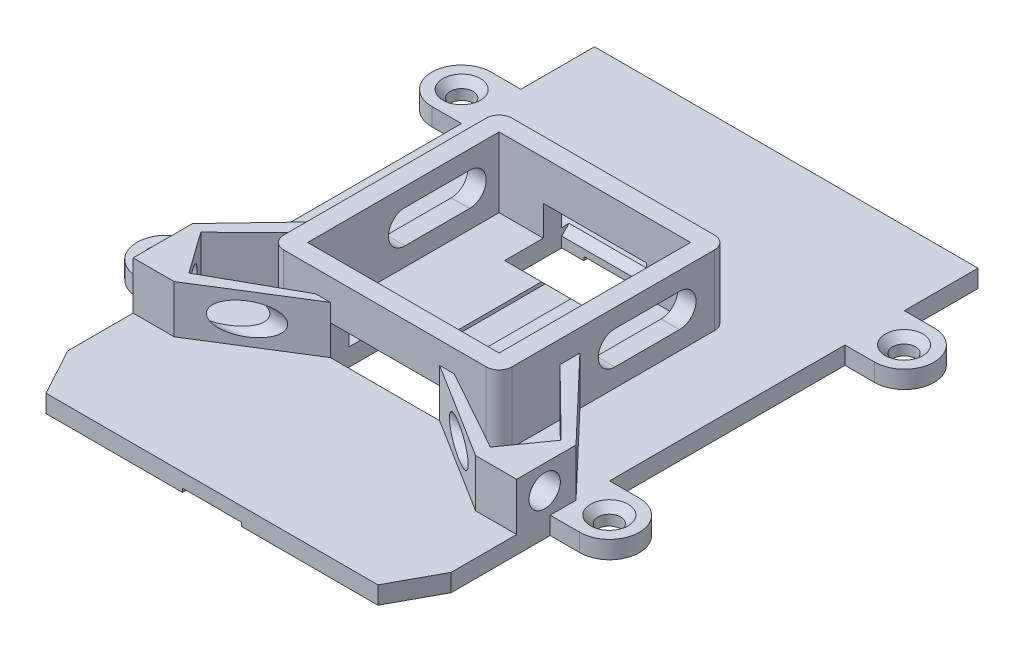
SolidWorks part; units mm, degrees
ref_plane "Front Plane" through (0, 0, 0) normal (0, 0, 1) x (1, 0, 0)
ref_plane "Top Plane" through (0, 0, 0) normal (0, 1, 0) x (1, 0, 0)
ref_plane "Right Plane" through (0, 0, 0) normal (1, 0, 0) x (0, 0, -1)
sketch "Sketch1" plane through (0, 0, 0) normal (0, 1, 0) x (1, 0, 0)
  line L0 (-26.0411, 38.9957) -> (26.0411, 38.9957)
  line L2 (26.0411, -32.5506) -> (22.5391, -38.9957)
  line L3 (22.5391, -38.9957) -> (-22.5391, -38.9957)
  line L4 (-22.5391, -38.9957) -> (-26.0411, -32.5506)
  line L7 (-30.0743, 28.9957) -> (-26.0411, 28.9957)
  line L9 (-26.0411, 20.9293) -> (-30.0408, 20.9293)
  line L19 (0, 50.1674) -> (0, -44.4088) construction
  line L28 (-26.0411, 38.9957) -> (-26.0411, 28.9957)
  line L32 (26.0411, 38.9957) -> (26.0411, 28.9957)
  line L35 (26.0411, 20.9293) -> (30.0408, 20.9293)
  line L36 (30.0743, 28.9957) -> (26.0411, 28.9957)
  line L41 (-30.0743, -11.0379) -> (-26.0411, -11.0379)
  line L42 (-26.0411, -19.1043) -> (-30.0408, -19.1043)
  line L46 (26.0411, -19.1043) -> (30.0408, -19.1043)
  line L47 (30.0743, -11.0379) -> (26.0411, -11.0379)
  line L49 (-26.0411, 20.9293) -> (-26.0411, -11.0379)
  line L50 (-26.0411, -19.1043) -> (-26.0411, -32.5506)
  line L51 (26.0411, -32.5506) -> (26.0411, -19.1043)
  line L52 (26.0411, -11.0379) -> (26.0411, 20.9293)
  circle A0 centre (-30.0411, 24.9624) radius 1.55
  arc A1 (-30.0743, 28.9957) -> (-30.0408, 20.9293) centre (-30.0743, 24.9624) ccw
  arc A8 (30.0743, 28.9957) -> (30.0408, 20.9293) centre (30.0743, 24.9624) cw
  circle A9 centre (30.0411, 24.9624) radius 1.55
  circle A12 centre (-30.0411, -15.0712) radius 1.55
  arc A13 (-30.0743, -11.0379) -> (-30.0408, -19.1043) centre (-30.0743, -15.0712) ccw
  arc A16 (30.0743, -11.0379) -> (30.0408, -19.1043) centre (30.0743, -15.0712) cw
  circle A17 centre (30.0411, -15.0712) radius 1.55
extrude "上盖底面" add sketch "Sketch1" along normal blind 2.4
sketch "Sketch2" plane through (0, 2.4, 0) normal (0, 1, 0) x (1, 0, 0)
  line L0 (-15.5, 15.5) -> (-15.5, -15.5)
  line L1 (-15.5, 15.5) -> (15.5, 15.5)
  line L2 (15.5, 15.5) -> (15.5, -15.5)
  line L3 (15.5, -15.5) -> (-15.5, -15.5)
  line L4 (-13, 13) -> (13, 13)
  line L5 (-13, 13) -> (-13, -13)
  line L6 (13, 13) -> (13, -13)
  line L7 (13, -13) -> (-13, -13)
extrude "GPS座" add sketch "Sketch2" along normal blind 9.5
fillet "圆角-GPS座" radius 1.75 4 edges at (15.5, 7.15, -15.5) (15.5, 7.15, 15.5) (-15.5, 7.15, 15.5) (-15.5, 7.15, -15.5)
chamfer "螺孔倒角" distance 1 angle 45 4 edges at (-30.0411, 2.4, -23.4124) (30.0411, 2.4, -26.5124) (30.0411, 2.4, 13.5212) (-30.0411, 2.4, 16.6212)
sketch "Sketch3" plane through (0, 2.4, 0) normal (0, 1, 0) x (1, 0, 0)
  line L23 (-24.4678, -16.0448) -> (-15.5, -7.2291)
  line L26 (-15.5, 13.75) -> (-15.5, -13.75) construction
  line L37 (0, 20.0815) -> (0, -29.1641) construction
  line L48 (-9.4136, -9.8097) -> (-9.4136, -15.5) construction
  line L49 (-15.5, -4.5293) -> (-7.4136, -4.5293) construction
  line L50 (-7.4136, -4.5293) -> (-7.4136, -15.5) construction
  line L51 (-15.5, -4.5293) -> (-15.5, -7.2291)
  line L59 (-7.4136, -15.5) -> (-20.4678, -23.6597)
  line L63 (-20.4678, -21.6597) -> (-24.4678, -16.0448)
  line L64 (-9.4136, -15.5) -> (-20.4678, -21.6597)
  line L65 (-15.5, -7.2291) -> (-9.4136, -9.8097) construction
  line L66 (-26.0411, -15.5968) -> (-26.0411, -23.6597)
  line L68 (-26.0411, -15.5968) -> (-15.5, -4.5293)
  line L69 (-26.0411, -23.6597) -> (-20.4678, -23.6597)
  line L70 (15.5, -7.2291) -> (9.4136, -9.8097) construction
  line L71 (7.4136, -4.5293) -> (7.4136, -15.5) construction
  line L72 (15.5, -4.5293) -> (7.4136, -4.5293) construction
  line L73 (9.4136, -9.8097) -> (9.4136, -15.5) construction
  line L83 (9.4136, -15.5) -> (7.4136, -15.5)
  line L86 (-9.4136, -15.5) -> (-7.4136, -15.5)
  line L87 (26.0411, -23.6597) -> (20.4678, -23.6597)
  line L88 (26.0411, -15.5968) -> (15.5, -4.5293)
  line L89 (26.0411, -15.5968) -> (26.0411, -23.6597)
  line L90 (9.4136, -15.5) -> (20.4678, -21.6597)
  line L91 (20.4678, -21.6597) -> (24.4678, -16.0448)
  line L92 (7.4136, -15.5) -> (20.4678, -23.6597)
  line L93 (15.5, -4.5293) -> (15.5, -7.2291)
  line L94 (24.4678, -16.0448) -> (15.5, -7.2291)
  point P21 (0, 0)
  point P26 (0, 0)
extrude "天线支架" add sketch "Sketch3" along normal blind 6.5
sketch "Sketch4" plane through (-26.0411, 0, 0) normal (-1, 0, 0) x (0, 0, 1)
  circle A0 centre (19.8523, 5.65) radius 2.125
extrude "支架穿孔" cut sketch "Sketch4" against normal through all
sketch "Sketch6" plane through (-15.5, 0, 0) normal (-1, 0, 0) x (0, 0, 1)
  line L3 (-9, 9.4) -> (-0.2207, 9.4)
  line L5 (-0.2207, 4.9) -> (-9, 4.9)
  arc A2 (-9, 9.4) -> (-9, 4.9) centre (-9, 7.15) ccw
  arc A3 (-0.2207, 9.4) -> (-0.2207, 4.9) centre (-0.2207, 7.15) cw
extrude "侧壁穿孔" cut sketch "Sketch6" against normal through all
sketch "Sketch7" plane through (0, 0, 0) normal (0, 1, 0) x (1, 0, 0)
  line L0 (0, 19.6177) -> (0, -19.7265) construction
  line L1 (7, 15.5) -> (7, 8.75)
  line L2 (13.75, 15.5) -> (-13.75, 15.5) construction
  line L3 (13.75, 15.5) -> (-13.75, 15.5) construction
  line L4 (-7, 15.5) -> (-7, 8.75)
  line L5 (-7, 15.5) -> (7, 15.5)
  line L6 (7, 8.75) -> (-7, 8.75)
  line L11 (-7.4136, -15.5) -> (7.4136, -15.5)
  line L12 (7.4136, -15.5) -> (7.4136, -8.75)
  line L13 (7.4136, -8.75) -> (-7.4136, -8.75)
  line L14 (-7.4136, -8.75) -> (-7.4136, -15.5)
extrude "线槽_侧壁" cut sketch "Sketch7" along normal blind 6.5
sketch "Sketch8" plane through (0, 2.4, 0) normal (0, 1, 0) x (1, 0, 0)
  line L0 (0, 18.7812) -> (0, -20.9983) construction
  line L2 (2, 8.75) -> (2, -8.75)
  line L7 (2, -8.75) -> (-2, -8.75)
  line L8 (7, 8.75) -> (-7, 8.75) construction
  line L9 (-2, 8.75) -> (2, 8.75)
  line L10 (-2, -8.75) -> (-2, 8.75)
  point P3 (0, 0)
  point P12 (0, 0)
extrude "线槽_底部" cut sketch "Sketch8" against normal blind 0.5
chamfer "线槽_倒角" distance 1 angle 45 3 edges at (4.5, 2.4, -8.75) (0, 2.4, -15.5) (-4.7068, 2.4, 8.75)
sketch "Sketch9" plane through (0, 0, 0) normal (0, -1, 0) x (1, 0, 0)
  line L0 (0, 43.4328) -> (0, -42.8472) construction
  line L1 (4, 38.9957) -> (4, -38.9957)
  line L2 (-22.5391, 38.9957) -> (22.5391, 38.9957) construction
  line L3 (-4, 38.9957) -> (4, 38.9957)
  line L4 (26.0411, -38.9957) -> (-26.0411, -38.9957) construction
  line L5 (4, -38.9957) -> (-4, -38.9957)
  line L6 (-4, 38.9957) -> (-4, -38.9957)
extrude "盖底线槽" cut sketch "Sketch9" against normal blind 0.5
